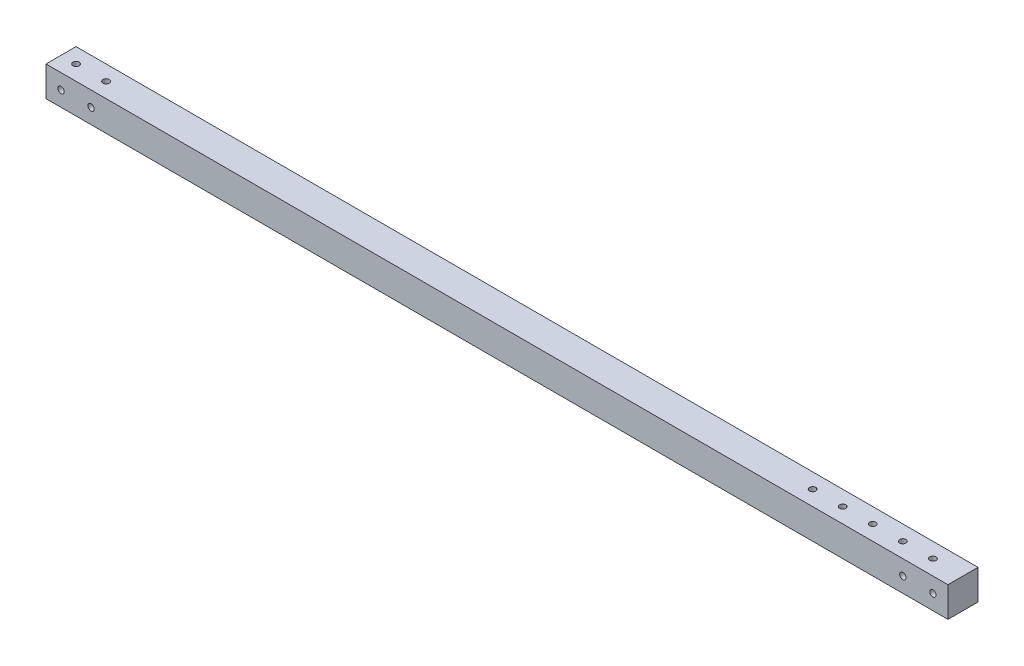
SolidWorks part; units mm, degrees
ref_plane "前视基准面" through (0, 0, 0) normal (0, 0, 1) x (1, 0, 0)
ref_plane "上视基准面" through (0, 0, 0) normal (0, 1, 0) x (1, 0, 0)
ref_plane "右视基准面" through (0, 0, 0) normal (1, 0, 0) x (0, 0, -1)
sketch "草图1" plane through (0, 0, 0) normal (1, 0, 0) x (0, 0, -1)
  line L1 (-10, 10) -> (10, 10)
  line L2 (-10, 10) -> (-10, -10)
  line L3 (-10, -10) -> (10, -10)
  line L4 (10, 10) -> (10, -10)
  line L5 (-10, 10) -> (10, -10) construction
  line L6 (-10, -10) -> (10, 10) construction
  point P0 (0, 0)
  dimension "D1" = 20
  dimension "D2" = 20
extrude "凸台-拉伸1" add sketch "草图1" along normal blind 600
sketch "草图2" plane through (0, 0, 10) normal (0, 0, 1) x (1, 0, 0)
  line L0 (0, 10) -> (0, -10) construction
  line L1 (600, 10) -> (0, 10) construction
  line L2 (300, 10) -> (300, -10) construction
  line L3 (600, -10) -> (0, -10) construction
  circle A0 centre (10, 0) radius 2.1
  circle A2 centre (30, 0) radius 2.1
  circle A4 centre (50, 0) radius 2.1 [skipped]
  circle A5 centre (570, 0) radius 2.1
  circle A6 centre (590, 0) radius 2.1
  dimension "D1" = 10
  dimension "D3" = 4.2
  dimension "D2" = 10
  dimension "D5" = 20
  dimension "D4" = 3
extrude "切除-拉伸1" cut sketch "草图2" against normal through all
sketch "草图3" plane through (0, 10, 0) normal (0, 1, 0) x (1, 0, 0)
  line L0 (0, 10) -> (0, -10) construction
  line L1 (600, 10) -> (0, 10) construction
  circle A0 centre (10, 0) radius 2.1
  circle A1 centre (30, 0) radius 2.1
  dimension "D1" = 10
  dimension "D3" = 4.2
  dimension "D4" = 4.2
  dimension "D2" = 10
  dimension "D5" = 20
extrude "切除-拉伸2" cut sketch "草图3" against normal through all
sketch "草图4" plane through (0, 10, 0) normal (0, 1, 0) x (1, 0, 0)
  line L0 (600, 10) -> (0, 10) construction
  line L1 (600, 10) -> (600, -10) construction
  circle A0 centre (580, 0) radius 2.1
  circle A1 centre (560, 0) radius 2.1
  circle A2 centre (540, 0) radius 2.1
  circle A3 centre (520, 0) radius 2.1
  circle A4 centre (500, 0) radius 2.1
  dimension "D1" = 10
  dimension "D3" = 4.2
  dimension "D2" = 20
  dimension "D5" = 20
  dimension "D4" = 5
extrude "切除-拉伸3" cut sketch "草图4" against normal through all
